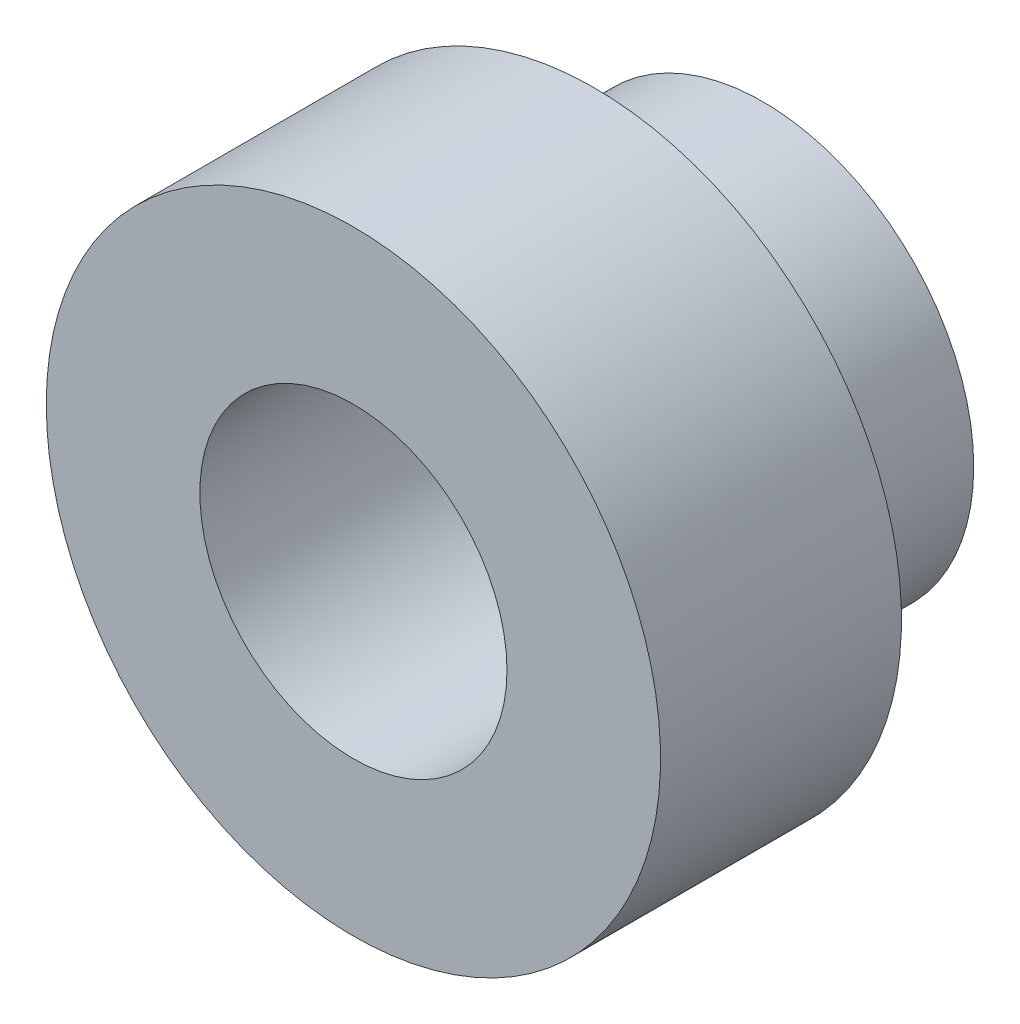
SolidWorks part; units mm, degrees
ref_plane "Front Plane" through (0, 0, 0) normal (0, 0, 1) x (1, 0, 0)
ref_plane "Top Plane" through (0, 0, 0) normal (0, 1, 0) x (1, 0, 0)
ref_plane "Right Plane" through (0, 0, 0) normal (1, 0, 0) x (0, 0, -1)
ref_plane "Plane1" through (0, 0, 0) normal (0, -1, 0) x (1, 0, 0)
sketch "Sketch1" plane through (0, 0, 0) normal (0, -1, 0) x (1, 0, 0)
  line L0 (2.55, 3.4) -> (0, 3.4)
  line L1 (0, 3.4) -> (0, 0)
  line L2 (0, 0) -> (1.75, 0)
  line L3 (1.75, 0) -> (1.75, 1.4)
  line L4 (1.75, 1.4) -> (2.55, 1.4)
  line L5 (2.55, 1.4) -> (2.55, 3.4)
  line L6 (0, 2) -> (0, 0) construction
  dimension "D1" = 5.1
  dimension "D2" = 3.4
  dimension "D3" = 3.5
  dimension "D5" = 2
revolve "Revolve1" add sketch "Sketch1" angle 360 about L6
hole_wizard "HoleWzd1" positions "Sketch2" profile "Sketch4" legacy end condition through all
sketch "Sketch2" plane through (0, 0, 3.4) normal (0, 0, 1) x (1, 0, 0)
  point P0 (0, 0)
sketch "Sketch4" plane through (0, 0, 3.4) normal (1, 0, 0) x (0, -1, 0)
  line L0 (0, 0) -> (0, 3.4)
  line L1 (0, 3.4) -> (1.275, 3.4)
  line L2 (1.275, 3.4) -> (1.275, 0)
  line L3 (1.275, 0) -> (0, 0)
  line L4 (0, 110) -> (0, -10) construction
  dimension "Diameter" = 2.55
  dimension "Depth" = 3.4
